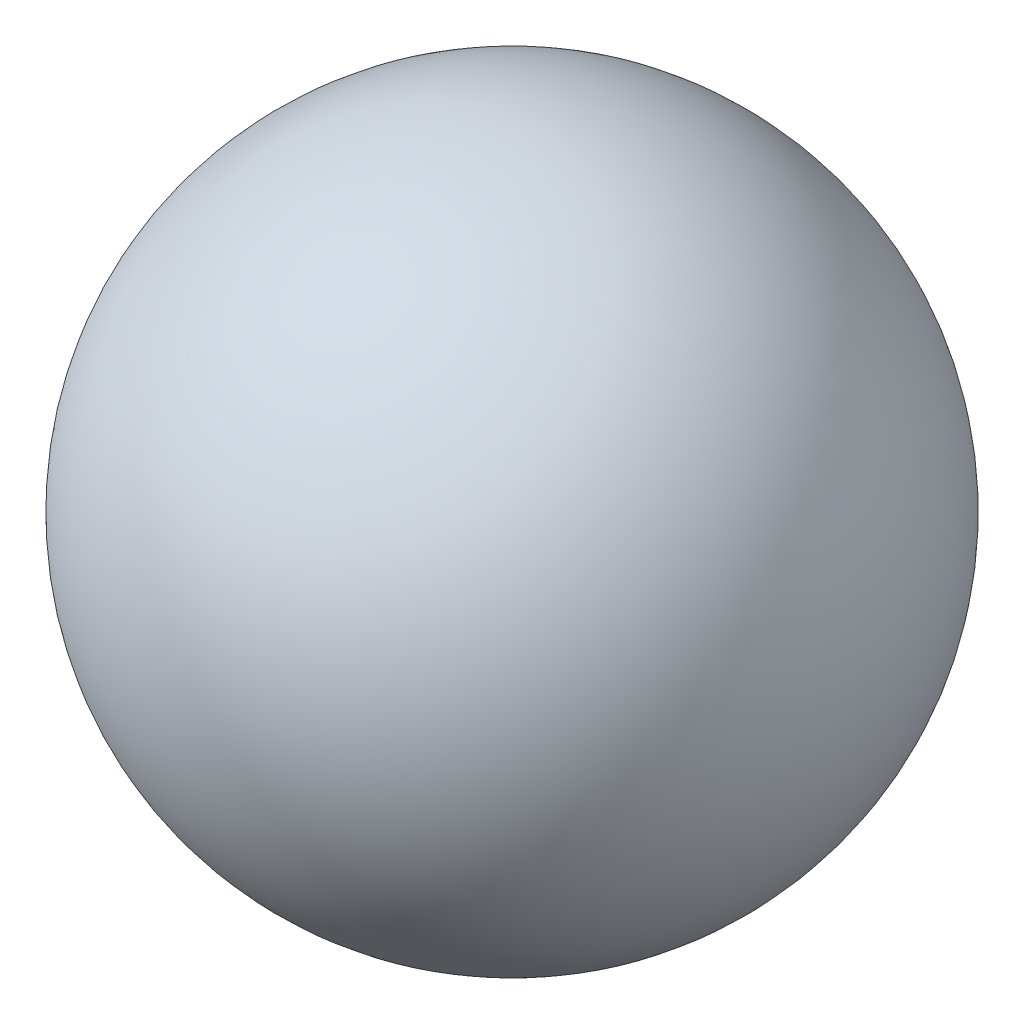
SolidWorks part; units mm, degrees
material "Rubber"
ref_plane "Front Plane" through (0, 0, 0) normal (0, 0, 1) x (1, 0, 0)
ref_plane "Top Plane" through (0, 0, 0) normal (0, 1, 0) x (1, 0, 0)
ref_plane "Right Plane" through (0, 0, 0) normal (1, 0, 0) x (0, 0, -1)
sketch "Sketch1" plane through (0, 0, 0) normal (0, 0, 1) x (1, 0, 0)
  line L0 (0, 36.5) -> (0, -36.5)
  arc A0 (0, -36.5) -> (0, 36.5) centre (0, 0) ccw
  dimension "D1" = 73
revolve "Revolve1" add sketch "Sketch1" angle 360 about L0
